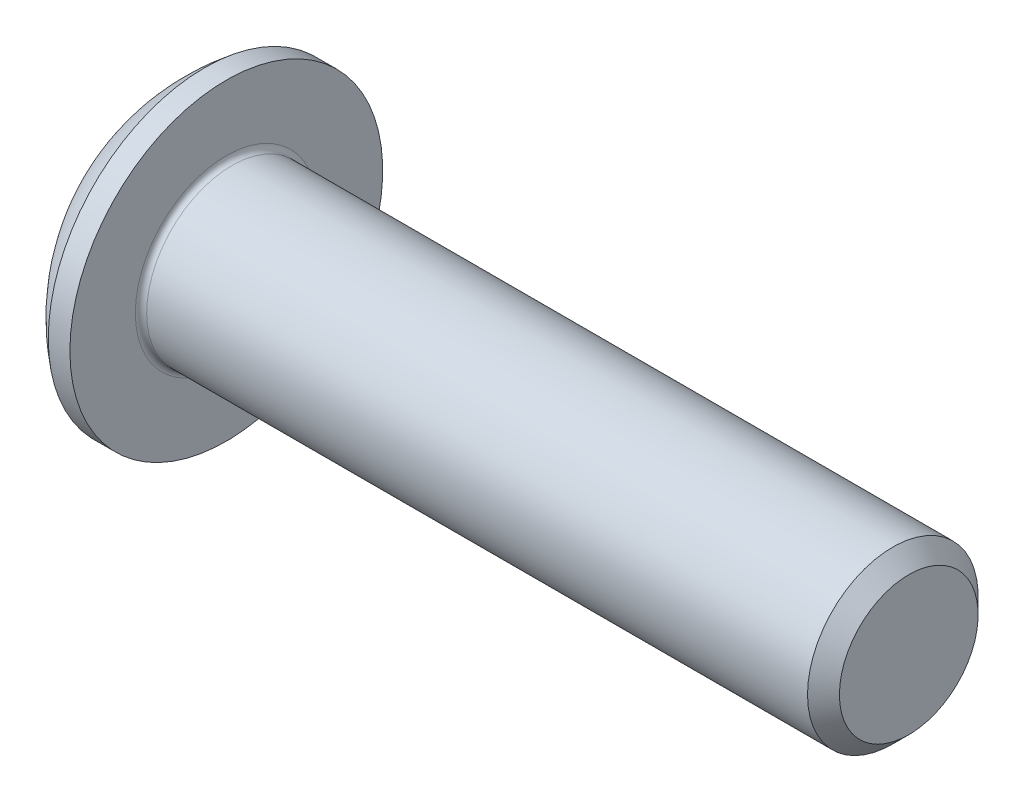
SolidWorks part; units mm, degrees
ref_plane "Plane1" through (0, 0, 0) normal (0, 0, 1) x (1, 0, 0)
ref_plane "Plane2" through (0, 0, 0) normal (0, 1, 0) x (1, 0, 0)
ref_plane "Plane3" through (0, 0, 0) normal (1, 0, 0) x (0, 0, -1)
sketch "BodySke" plane through (0, 0, 0) normal (0, 0, 1) x (1, 0, 0)
  line L0 (13.45, 0) -> (13.45, 1.2195)
  line L1 (13.1695, 1.5) -> (1.45, 1.5)
  line L2 (1.45, 1.5) -> (1.45, 2.75)
  line L3 (1.45, 2.75) -> (1.07, 2.75)
  line L4 (0, 0) -> (101.6, 0) construction
  line L5 (1.45, -2.75) -> (1.07, -2.75) construction
  line L6 (55.6768, -1.5) -> (1.45, -1.5) construction
  line L7 (13.45, 0) -> (0, 0)
  line L8 (0, 1.375) -> (0, -1.375) construction
  line L9 (0, 0) -> (0, 1.375)
  line L10 (13.45, 1.2195) -> (13.1695, 1.5)
  line L11 (13.45, -1.2195) -> (13.1695, -1.5) construction
  line L12 (1.95, 9.525) -> (1.95, -1.5) construction
  line L13 (1.45, 9.525) -> (1.45, -1.5) construction
  arc A1 (0, 1.375) -> (1.07, 2.75) centre (3.1854, 0) cw
  dimension "D1" = 2.75
  dimension "Diameter" = 3
  dimension "Length" = 12
  dimension "Head_dia" = 5.5
  dimension "Head_ht" = 1.45
  dimension "Head_side_ht" = 0.38
  dimension "Minor_dia" = 2.439
  dimension "Body_ch_ang" = 45
  dimension "Advance" = 0.5
  dimension "Thread_nom" = 12
revolve "BaseBody" add sketch "BodySke" angle 360 about L4
cosmetic thread "ThreadCosmetic" parameters "Thread_length"=11, "Thread_minor"=2.439
fillet "Fillet1" radius 0.1 1 edges at (1.45, 0, 1.5)
sketch "Sketch2" plane through (0, 0, 0) normal (0, 0, 1) x (1, 0, 0)
  line L0 (0, 1) -> (1.04, 1)
  line L1 (1.04, 1) -> (1.6174, 0)
  line L3 (1.6174, 0) -> (0, 0)
  line L4 (0, 0) -> (0, 1)
  line L5 (0, -1) -> (1.04, -1) construction
  line L6 (0, 0) -> (47.625, 0) construction
  dimension "D2" = 60
  dimension "PreBroach_depth" = 1.04
  dimension "PreBroach_dia" = 2
revolve "PreBroach" cut sketch "Sketch2" angle 360 about L6
sketch "Sketch3" plane through (0, 0, 0) normal (1, 0, 0) x (0, 0, -1)
  line L0 (-1, -0.5774) -> (-1, 0.5774)
  line L1 (-1, 0.5774) -> (0, 1.1547)
  line L2 (0, 1.1547) -> (1, 0.5774)
  line L3 (1, 0.5774) -> (1, -0.5774)
  line L4 (1, -0.5774) -> (0, -1.1547)
  line L5 (0, -1.1547) -> (-1, -0.5774)
  dimension "D1" = 1
  dimension "D2" = 1
  dimension "D3" = 2
  dimension "Hex_size" = 2
extrude "Hex" cut sketch "Sketch3" along normal blind 1.04
sketch "ThdSchSke" plane through (0, 0, 0) normal (0, 0, 1) x (1, 0, 0)
  line L0 (2.45, -1.2195) -> (2.2536, -1.5)
  line L1 (2.45, -1.2195) -> (2.6464, -1.5)
  line L2 (2.6464, -1.5) -> (2.6464, -1.875)
  line L3 (-3.175, 0) -> (5.1513, 0) construction
  line L5 (2.6464, -1.875) -> (2.2536, -1.875)
  line L6 (2.2536, -1.875) -> (2.2536, -1.5)
  dimension "Thread_minor" = 2.439
  dimension "Diameter" = 3
  dimension "Start" = 2.45
  dimension "SideAngle" = 55
  dimension "VeeAngle" = 70
  dimension "Overcut" = 3.75
revolve "ThreadSchematic" [suppressed] cut sketch "ThdSchSke" angle 360 about L3
pattern_linear "ThdSchPat" [suppressed]
equation "\"D1@BodySke\" = \"Head_dia@BodySke\" * .5"
equation "\"Thread_minor@ThreadCosmetic\" = \"Minor_dia@BodySke\""
equation "\"D1@Sketch3\" = \"Hex_size@Sketch3\" / 2"
equation "\"D2@Sketch3\" = \"D1@Sketch3\""
equation "\"D3@Sketch3\" = \"Hex_size@Sketch3\""
equation "\"Thread_length@ThreadCosmetic\" = ((sgn( (\"Length@BodySke\" - \"Advance@BodySke\" * 2.0) - \"Thread_nom@BodySke\" )-1)*( (\"Length@BodySke\" - \"Advance@BodySke\" * 2.0) - \"Thread_nom@BodySke\" ))/-2+ \"Thread_nom@BodySke\""
equation "\"Thread_minor@ThdSchSke\" = \"Minor_dia@BodySke\""
equation "\"Diameter@ThdSchSke\" = \"Diameter@BodySke\""
equation "\"Overcut@ThdSchSke\" = \"Diameter@BodySke\" * 1.25"
equation "\"Start@ThdSchSke\" = \"Head_ht@BodySke\" + \"Length@BodySke\" - \"Thread_length@ThreadCosmetic\"  '---Non-countersunk---"
equation "\"Num_threads@ThdSchPat\" = int( \"Thread_length@ThreadCosmetic\" / \"Advance@BodySke\" + 0.999 )  + 1"
equation "\"Advance@ThdSchPat\" = \"Thread_length@ThreadCosmetic\" /  (\"Num_threads@ThdSchPat\" - 1) 'relax it"
equation "\"Num_threads@ThdSchPat\" = \"Num_threads@ThdSchPat\" - sgn( \"Num_threads@ThdSchPat\" - 1) '---chamfered tips only---"
